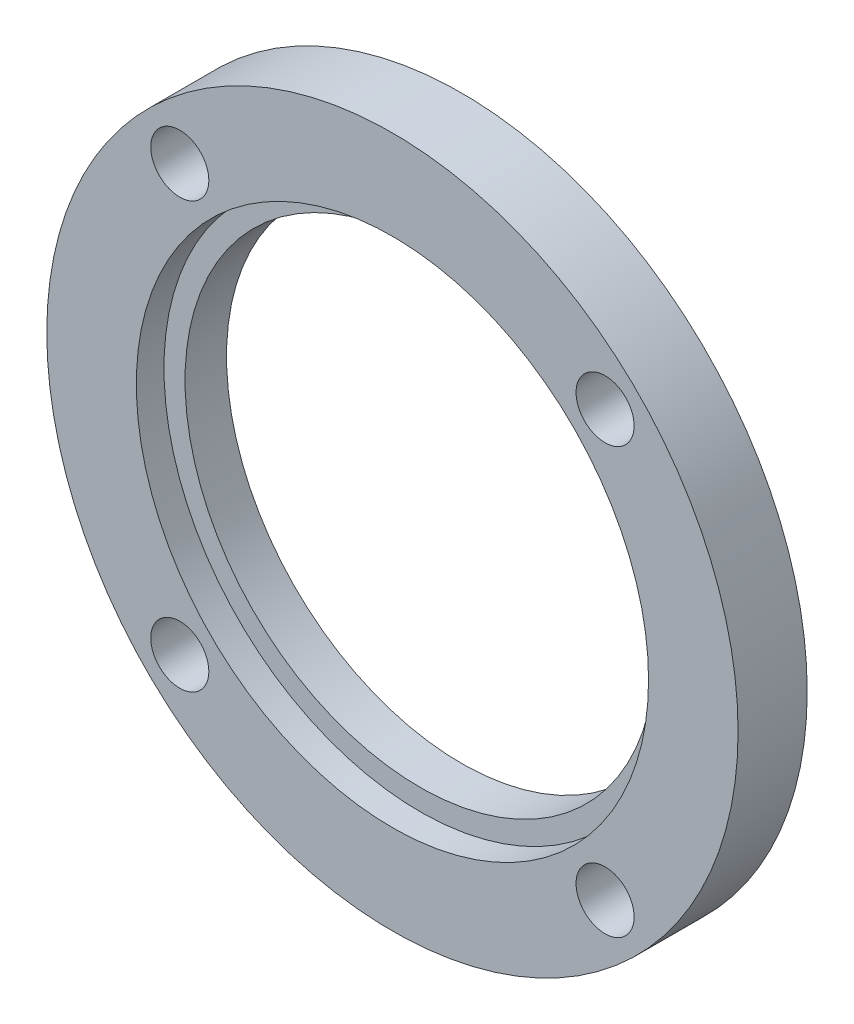
SolidWorks part; units mm, degrees
material "5052-H34"
ref_plane "正面" through (0, 0, 0) normal (0, 0, 1) x (1, 0, 0)
ref_plane "平面" through (0, 0, 0) normal (0, 1, 0) x (1, 0, 0)
ref_plane "右側面" through (0, 0, 0) normal (1, 0, 0) x (0, 0, -1)
sketch "ｽｹｯﾁ1" plane through (0, 0, 0) normal (0, 0, 1) x (1, 0, 0)
  circle A0 centre (0, 0) radius 25
  dimension "D1" = 50
extrude "ﾎﾞｽ - 押し出し1" add sketch "ｽｹｯﾁ1" along normal blind 5
sketch "ｽｹｯﾁ2" plane through (0, 0, 5) normal (0, 0, 1) x (1, 0, 0)
  circle A0 centre (0, 0) radius 18.525
  dimension "D1" = 37.05
extrude "ｶｯﾄ - 押し出し1" cut sketch "ｽｹｯﾁ2" against normal blind 2
sketch "ｽｹｯﾁ3" plane through (0, 0, 3) normal (0, 0, 1) x (1, 0, 0)
  circle A0 centre (0, 0) radius 17
  dimension "D1" = 34
extrude "ｶｯﾄ - 押し出し2" cut sketch "ｽｹｯﾁ3" against normal up to surface (3 mm away) up to face at (25, 0, 0)
sketch "ｽｹｯﾁ4" plane through (0, 0, 5) normal (0, 0, 1) x (1, 0, 0)
  line L0 (0, 0) -> (21.75, 0) construction
  line L1 (0, 0) -> (15.3796, 15.3796) construction
  circle A0 centre (0, 0) radius 21.75 construction
  circle A1 centre (15.3796, 15.3796) radius 2.1
  circle A2 centre (15.3796, -15.3796) radius 2.1
  circle A3 centre (-15.3796, -15.3796) radius 2.1
  circle A4 centre (-15.3796, 15.3796) radius 2.1
  dimension "D1" = 43.5
  dimension "D3" = 4.2
  dimension "D2" = 45
  dimension "D4" = 4
extrude "ｶｯﾄ - 押し出し3" cut sketch "ｽｹｯﾁ4" against normal up to surface (5 mm away) up to face at (17, 0, 0)
